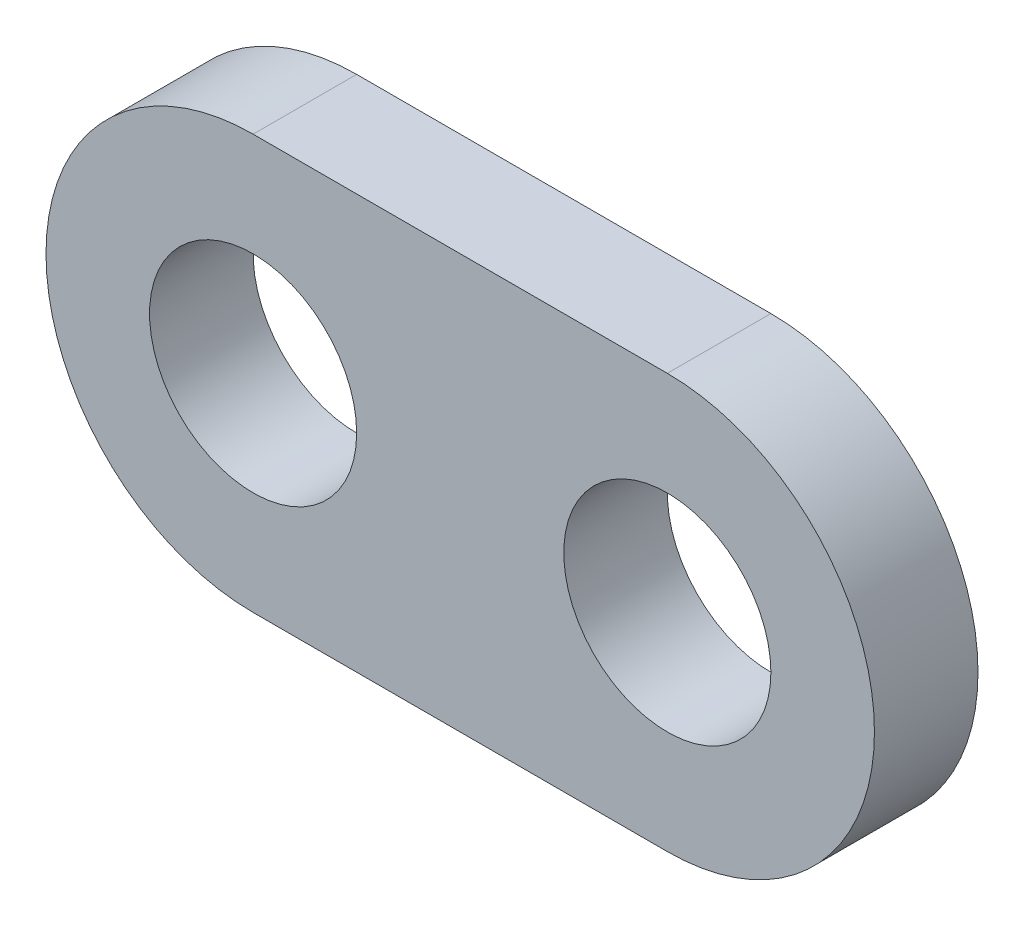
SolidWorks part; units mm, degrees
ref_plane "Front Plane" through (0, 0, 0) normal (0, 0, 1) x (1, 0, 0)
ref_plane "Top Plane" through (0, 0, 0) normal (0, 1, 0) x (1, 0, 0)
ref_plane "Right Plane" through (0, 0, 0) normal (1, 0, 0) x (0, 0, -1)
sketch "Sketch1" plane through (0, 0, 0) normal (0, 0, 1) x (1, 0, 0)
  line L0 (0, 0) -> (20, 0) construction
  line L1 (0, 10) -> (20, 10)
  line L2 (0, -10) -> (20, -10)
  arc A0 (0, 10) -> (0, -10) centre (0, 0) ccw
  arc A1 (20, -10) -> (20, 10) centre (20, 0) ccw
  circle A2 centre (0, 0) radius 5
  circle A3 centre (20, 0) radius 5
  point P3 (10, 0)
  dimension "D2" = 10
  dimension "D3" = 10
  dimension "D1" = 20
  dimension "D4" = 20
extrude "Boss-Extrude1" add sketch "Sketch1" along normal blind 5
